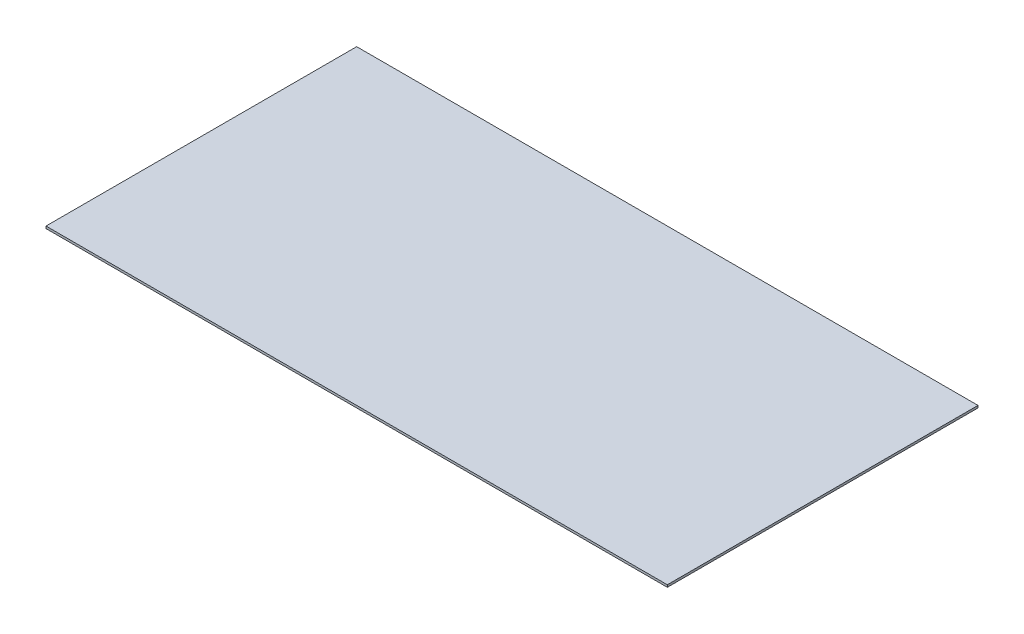
SolidWorks part; units mm, degrees
ref_plane "Спереди" through (0, 0, 0) normal (0, 0, 1) x (1, 0, 0)
ref_plane "Сверху" through (0, 0, 0) normal (0, 1, 0) x (1, 0, 0)
ref_plane "Справа" through (0, 0, 0) normal (1, 0, 0) x (0, 0, -1)
sketch "Эскиз1" plane through (0, 0, 0) normal (0, 1, 0) x (1, 0, 0)
  line L1 (1250, -625) -> (-1250, -625)
  line L2 (1250, -625) -> (1250, 625)
  line L3 (1250, 625) -> (-1250, 625)
  line L4 (-1250, -625) -> (-1250, 625)
  line L5 (1250, -625) -> (-1250, 625) construction
  line L6 (1250, 625) -> (-1250, -625) construction
  point P0 (0, 0)
  dimension "D1" = 2500
  dimension "D2" = 1250
extrude "Бобышка-Вытянуть1" add sketch "Эскиз1" along normal blind 9
